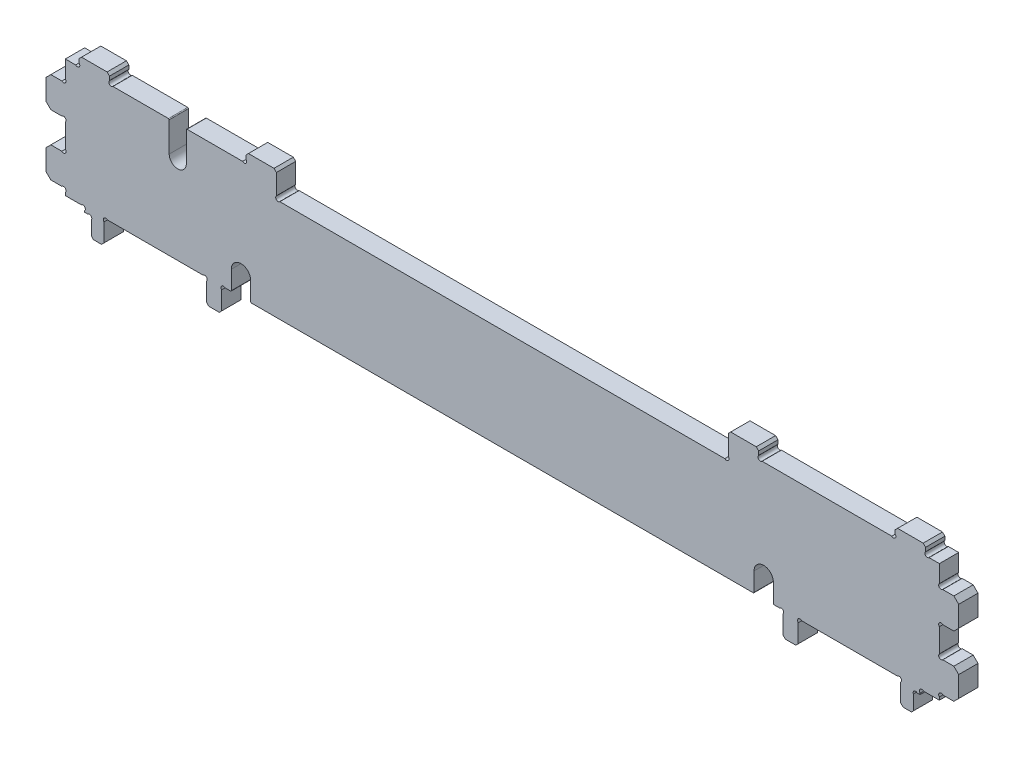
SolidWorks part; units mm, degrees
ref_plane "Front Plane" through (0, 0, 0) normal (0, 0, 1) x (1, 0, 0)
ref_plane "Top Plane" through (0, 0, 0) normal (0, 1, 0) x (1, 0, 0)
ref_plane "Right Plane" through (0, 0, 0) normal (1, 0, 0) x (0, 0, -1)
sketch "Model" plane through (0, 0, 0) normal (0, 0, 1) x (1, 0, 0)
  line L0 (138.1552, -67.6125) -> (138.949, -66.8188)
  line L1 (134.6215, -66.8188) -> (135.4153, -67.6125)
  line L2 (100.1328, -67.6125) -> (100.9265, -66.8188)
  line L3 (95.9265, -66.8188) -> (96.7203, -67.6125)
  line L4 (-89.3772, -67.6125) -> (-88.5835, -66.8188)
  line L5 (-93.5835, -66.8188) -> (-92.7897, -67.6125)
  line L6 (-128.0722, -67.6125) -> (-127.2785, -66.8188)
  line L7 (-131.5077, -66.8188) -> (-130.7139, -67.6125)
  line L8 (-146.3285, -56.025) -> (-144.741, -57.6125)
  line L9 (-144.741, -47.6125) -> (-146.3285, -49.2)
  line L10 (-146.3285, -36.025) -> (-144.741, -37.6125)
  line L11 (-144.741, -27.6125) -> (-146.3285, -29.2)
  line L12 (-134.6597, -17.6125) -> (-135.4535, -18.4063)
  line L13 (-125.4535, -18.4063) -> (-126.2472, -17.6125)
  line L14 (-79.7957, -17.6125) -> (-80.5895, -18.4063)
  line L15 (-70.5895, -18.4063) -> (-71.3832, -17.6125)
  line L16 (-69.4669, -26.1597) -> (76.81, -26.1597)
  line L17 (78.7263, -17.6125) -> (77.9325, -18.4063)
  line L18 (87.9325, -18.4063) -> (87.1388, -17.6125)
  line L19 (133.5903, -17.6125) -> (132.7965, -18.4063)
  line L20 (142.7965, -18.4063) -> (142.0028, -17.6125)
  line L21 (153.6715, -29.2) -> (152.084, -27.6125)
  line L22 (152.084, -37.6125) -> (153.6715, -36.025)
  line L23 (153.6715, -49.2) -> (152.084, -47.6125)
  line L24 (152.084, -57.6125) -> (153.6715, -56.025)
  line L25 (102.0491, -59.6877) -> (133.499, -59.6877)
  line L26 (100.9265, -66.8188) -> (100.9265, -60.8103)
  line L27 (96.7203, -67.6125) -> (100.1328, -67.6125)
  line L28 (95.9265, -60.8103) -> (95.9265, -66.8188)
  line L29 (-87.4609, -59.6877) -> (94.804, -59.6877)
  line L30 (-88.5835, -66.8188) -> (-88.5835, -60.8103)
  line L31 (-92.7897, -67.6125) -> (-89.3772, -67.6125)
  line L32 (-93.5835, -60.8103) -> (-93.5835, -66.8188)
  line L33 (-126.1559, -59.6877) -> (-94.706, -59.6877)
  line L34 (-127.2785, -66.8188) -> (-127.2785, -60.8103)
  line L35 (-130.7139, -67.6125) -> (-128.0722, -67.6125)
  line L36 (-131.5077, -62.3851) -> (-131.5077, -66.8188)
  line L37 (-133.6285, -61.2625) -> (-132.6302, -61.2625)
  line L38 (-133.6285, -60.8103) -> (-133.6285, -61.2625)
  line L39 (-139.9785, -59.6877) -> (-134.751, -59.6877)
  line L40 (-139.9785, -58.7351) -> (-139.9785, -59.6877)
  line L41 (-144.741, -57.6125) -> (-141.101, -57.6125)
  line L42 (-146.3285, -49.2) -> (-146.3285, -56.025)
  line L43 (-141.101, -47.6125) -> (-144.741, -47.6125)
  line L44 (-139.9785, -38.7351) -> (-139.9785, -46.49)
  line L45 (-144.741, -37.6125) -> (-141.101, -37.6125)
  line L46 (-146.3285, -29.2) -> (-146.3285, -36.025)
  line L47 (-141.101, -27.6125) -> (-144.741, -27.6125)
  line L48 (-139.9785, -20.7875) -> (-139.9785, -26.49)
  line L49 (-136.576, -20.7875) -> (-139.9785, -20.7875)
  line L50 (-135.4535, -18.4063) -> (-135.4535, -19.665)
  line L51 (-126.2472, -17.6125) -> (-134.6597, -17.6125)
  line L52 (-125.4535, -19.665) -> (-125.4535, -18.4063)
  line L53 (-105.5215, -20.7875) -> (-124.3309, -20.7875)
  line L54 (-105.5215, -29.665) -> (-105.5215, -20.7875)
  line L55 (-101.644, -30.7875) -> (-104.3989, -30.7875)
  line L56 (-100.5215, -20.7875) -> (-100.5215, -29.665)
  line L57 (-81.712, -20.7875) -> (-100.5215, -20.7875)
  line L58 (-80.5895, -18.4063) -> (-80.5895, -19.665)
  line L59 (-71.3832, -17.6125) -> (-79.7957, -17.6125)
  line L60 (-70.5895, -25.0372) -> (-70.5895, -18.4063)
  line L61 (77.9325, -18.4063) -> (77.9325, -25.0372)
  line L62 (87.1388, -17.6125) -> (78.7263, -17.6125)
  line L63 (87.9325, -19.665) -> (87.9325, -18.4063)
  line L64 (131.674, -20.7875) -> (89.0551, -20.7875)
  line L65 (132.7965, -18.4063) -> (132.7965, -19.665)
  line L66 (142.0028, -17.6125) -> (133.5903, -17.6125)
  line L67 (142.7965, -19.665) -> (142.7965, -18.4063)
  line L68 (147.3215, -20.7875) -> (143.9191, -20.7875)
  line L69 (147.3215, -26.49) -> (147.3215, -20.7875)
  line L70 (152.084, -27.6125) -> (148.4441, -27.6125)
  line L71 (153.6715, -36.025) -> (153.6715, -29.2)
  line L72 (148.4441, -37.6125) -> (152.084, -37.6125)
  line L73 (147.3215, -46.49) -> (147.3215, -38.7351)
  line L74 (152.084, -47.6125) -> (148.4441, -47.6125)
  line L75 (153.6715, -56.025) -> (153.6715, -49.2)
  line L76 (148.4441, -57.6125) -> (152.084, -57.6125)
  line L77 (147.3215, -59.6877) -> (147.3215, -58.7351)
  line L78 (142.0941, -59.6877) -> (147.3215, -59.6877)
  line L79 (140.9715, -61.2625) -> (140.9715, -60.8103)
  line L80 (140.0715, -61.2625) -> (140.9715, -61.2625)
  line L81 (138.949, -66.8188) -> (138.949, -62.3851)
  line L82 (135.4153, -67.6125) -> (138.1552, -67.6125)
  line L83 (134.6215, -60.8103) -> (134.6215, -66.8188)
  arc A0 (-70.5895, -25.0372) -> (-69.4669, -26.1597) centre (-70.0282, -25.5985) ccw
  arc A1 (76.81, -26.1597) -> (77.9325, -25.0372) centre (77.3713, -25.5985) ccw
  arc A2 (102.0491, -59.6877) -> (100.9265, -60.8103) centre (101.4878, -60.249) ccw
  arc A3 (95.9265, -60.8103) -> (94.804, -59.6877) centre (95.3653, -60.249) ccw
  arc A4 (-87.4609, -59.6877) -> (-88.5835, -60.8103) centre (-88.0222, -60.249) ccw
  arc A5 (-93.5835, -60.8103) -> (-94.706, -59.6877) centre (-94.1447, -60.249) ccw
  arc A6 (-126.1559, -59.6877) -> (-127.2785, -60.8103) centre (-126.7172, -60.249) ccw
  arc A7 (-131.5077, -62.3851) -> (-132.6302, -61.2625) centre (-132.069, -61.8238) ccw
  arc A8 (-133.6285, -60.8103) -> (-134.751, -59.6877) centre (-134.1897, -60.249) ccw
  arc A9 (-139.9785, -58.7351) -> (-141.101, -57.6125) centre (-140.5397, -58.1738) ccw
  arc A10 (-141.101, -47.6125) -> (-139.9785, -46.49) centre (-140.5397, -47.0513) ccw
  arc A11 (-139.9785, -38.7351) -> (-141.101, -37.6125) centre (-140.5397, -38.1738) ccw
  arc A12 (-141.101, -27.6125) -> (-139.9785, -26.49) centre (-140.5397, -27.0513) ccw
  arc A13 (-136.576, -20.7875) -> (-135.4535, -19.665) centre (-136.0147, -20.2263) ccw
  arc A14 (-125.4535, -19.665) -> (-124.3309, -20.7875) centre (-124.8922, -20.2263) ccw
  arc A15 (-105.5215, -29.665) -> (-104.3989, -30.7875) centre (-104.9602, -30.2263) ccw
  arc A16 (-101.644, -30.7875) -> (-100.5215, -29.665) centre (-101.0827, -30.2263) ccw
  arc A17 (-81.712, -20.7875) -> (-80.5895, -19.665) centre (-81.1507, -20.2263) ccw
  arc A18 (87.9325, -19.665) -> (89.0551, -20.7875) centre (88.4938, -20.2263) ccw
  arc A19 (131.674, -20.7875) -> (132.7965, -19.665) centre (132.2353, -20.2263) ccw
  arc A20 (142.7965, -19.665) -> (143.9191, -20.7875) centre (143.3578, -20.2263) ccw
  arc A21 (147.3215, -26.49) -> (148.4441, -27.6125) centre (147.8828, -27.0513) ccw
  arc A22 (148.4441, -37.6125) -> (147.3215, -38.7351) centre (147.8828, -38.1738) ccw
  arc A23 (147.3215, -46.49) -> (148.4441, -47.6125) centre (147.8828, -47.0513) ccw
  arc A24 (148.4441, -57.6125) -> (147.3215, -58.7351) centre (147.8828, -58.1738) ccw
  arc A25 (142.0941, -59.6877) -> (140.9715, -60.8103) centre (141.5328, -60.249) ccw
  arc A26 (140.0715, -61.2625) -> (138.949, -62.3851) centre (139.5102, -61.8238) ccw
  arc A27 (134.6215, -60.8103) -> (133.499, -59.6877) centre (134.0603, -60.249) ccw
extrude "Boss-Extrude1" add sketch "Model" along normal blind 6.35
sketch "Sketch3" plane through (0, 0, 6.35) normal (0, 0, 1) x (1, 0, 0)
  line L0 (-131.3553, -62.1713) -> (-131.3553, -66.9712)
  line L1 (-131.5077, -66.8188) -> (-130.7139, -67.6125) construction
  line L2 (-131.5077, -62.3851) -> (-131.5077, -66.8188) construction
  line L3 (-131.5077, -62.3851) -> (-131.5077, -66.8188)
  line L4 (-131.5077, -66.8188) -> (-131.3553, -66.9712)
  line L5 (138.7966, -62.1713) -> (138.7966, -66.9712)
  line L7 (138.1552, -67.6125) -> (138.949, -66.8188) construction
  line L8 (138.949, -66.8188) -> (138.949, -62.3851) construction
  line L9 (138.7966, -66.9712) -> (138.949, -66.8188)
  line L10 (138.949, -66.8188) -> (138.949, -62.3851)
  arc A0 (-131.5077, -62.3851) -> (-132.6302, -61.2625) centre (-132.069, -61.8238) ccw construction
  arc A1 (-131.5077, -62.3851) -> (-131.3553, -62.1713) centre (-132.069, -61.8238) ccw
  arc A4 (140.0715, -61.2625) -> (138.949, -62.3851) centre (139.5102, -61.8238) ccw construction
  arc A5 (138.7966, -62.1713) -> (138.949, -62.3851) centre (139.5102, -61.8238) ccw
  point P9 (138.7229, -61.9242)
  point P12 (138.7172, -67.0506)
  point P16 (138.7172, -61.79)
  dimension "D1" = 0.1524
  dimension "D2" = 0.1524
extrude "Cut-Extrude2" cut sketch "Sketch3" against normal through all
sketch "Sketch4" plane through (0, 0, 6.35) normal (0, 0, 1) x (1, 0, 0)
  line L0 (-87.4609, -59.6877) -> (94.804, -59.6877) construction
  line L1 (-85.4085, -59.6877) -> (-79.0585, -59.6877)
  line L2 (-85.4085, -59.6877) -> (-85.4085, -53.3377)
  line L4 (-79.0585, -59.6877) -> (-79.0585, -53.3377)
  line L5 (-88.5835, -66.8188) -> (-88.5835, -60.8103) construction
  line L6 (-139.9785, -20.7875) -> (147.3215, -59.6877) construction
  line L7 (3.6715, -54.3155) -> (3.6715, -26.1597) construction
  line L8 (76.81, -26.1597) -> (-69.4669, -26.1597) construction
  line L9 (86.4015, -59.6877) -> (86.4015, -53.3377)
  line L10 (92.7515, -59.6877) -> (92.7515, -53.3377)
  line L11 (92.7515, -59.6877) -> (86.4015, -59.6877)
  arc A0 (-79.0585, -53.3377) -> (-85.4085, -53.3377) centre (-82.2335, -53.3377) ccw
  arc A1 (86.4015, -53.3377) -> (92.7515, -53.3377) centre (89.5765, -53.3377) cw
  point P14 (3.6715, -54.3155)
  point P19 (3.6715, -40.2376)
  dimension "D2" = 6.35
  dimension "D1" = 3.175
  dimension "D3" = 6.35
  dimension "D4" = 6.35
extrude "Cut-Extrude3" cut sketch "Sketch4" against normal through all
sketch "Sketch6" plane through (0, 0, 6.35) normal (0, 0, 1) x (1, 0, 0)
  line L0 (-101.644, -30.7875) -> (-104.3989, -30.7875) construction
  line L1 (-81.712, -20.7875) -> (-100.5215, -20.7875) construction
  line L3 (-105.8335, -30.7875) -> (-105.8335, -20.7875)
  line L4 (-105.8335, -20.7875) -> (-100.2094, -20.7875)
  line L5 (-100.2094, -30.7875) -> (-100.2094, -20.7875)
  arc A0 (-105.8335, -30.7875) -> (-100.2094, -30.7875) centre (-103.0215, -30.7875) ccw
  arc A1 (-101.644, -30.7875) -> (-100.5215, -29.665) centre (-101.0827, -30.2263) ccw construction
  point P13 (-100.2094, -30.7875)
extrude "Cut-Extrude4" cut sketch "Sketch6" against normal through all
fillet "Fillet1" radius 0.254 6 edges at (86.4015, -59.6877, 3.175) (92.7515, -59.6877, 3.175) (-79.0585, -59.6877, 3.175) (-85.4085, -59.6877, 3.175) (-105.8335, -20.7875, 3.175) (-100.2094, -20.7875, 3.175)
